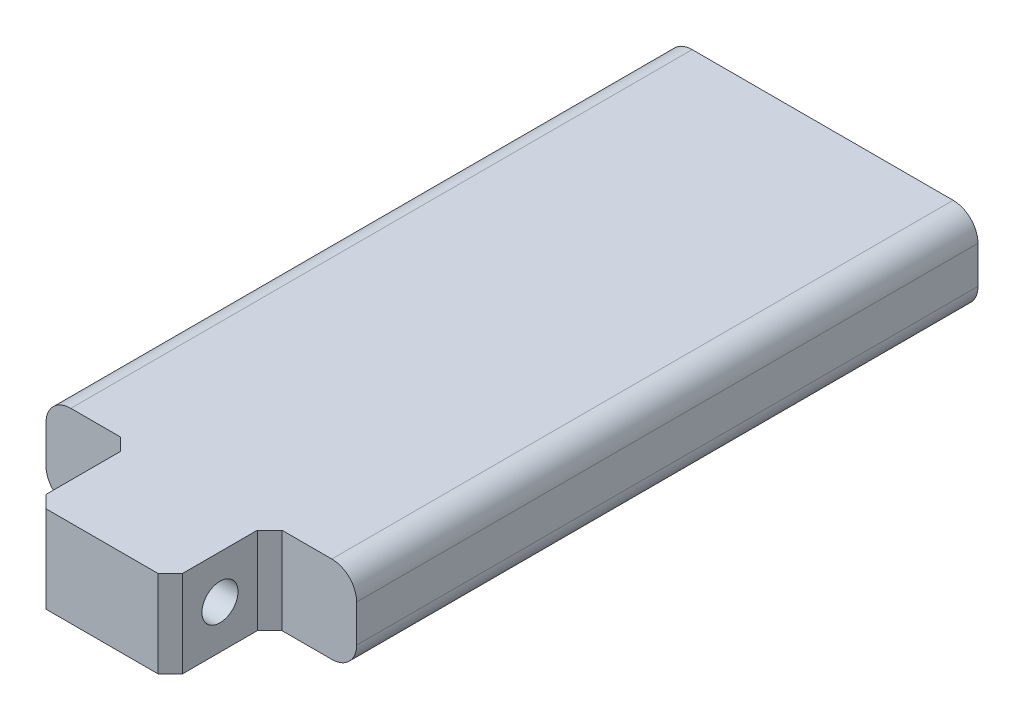
SolidWorks part; units mm, degrees
material "AISI 1020"
ref_plane "Front Plane" through (0, 0, 0) normal (0, 0, 1) x (1, 0, 0)
ref_plane "Top Plane" through (0, 0, 0) normal (0, 1, 0) x (1, 0, 0)
ref_plane "Right Plane" through (0, 0, 0) normal (1, 0, 0) x (0, 0, -1)
sketch "Sketch1" plane through (0, 0, 0) normal (0, 0, 1) x (1, 0, 0)
  line L1 (-12.5, -3.5) -> (12.5, -3.5)
  line L2 (-12.5, -3.5) -> (-12.5, 3.5)
  line L3 (-12.5, 3.5) -> (12.5, 3.5)
  line L4 (12.5, -3.5) -> (12.5, 3.5)
  line L5 (-12.5, -3.5) -> (12.5, 3.5) construction
  line L6 (-12.5, 3.5) -> (12.5, -3.5) construction
  point P0 (0, 0)
  dimension "D1" = 25
  dimension "D2" = 7
extrude "Boss-Extrude1" add sketch "Sketch1" along normal blind 58
sketch "Sketch2" plane through (0, 3.5, 0) normal (0, 1, 0) x (1, 0, 0)
  line L2 (-12.5, -58) -> (-5.5, -58)
  line L4 (-12.5, -58) -> (-12.5, -50)
  line L5 (-12.5, -50) -> (-5.5, -50)
  line L6 (-5.5, -58) -> (-5.5, -50)
  line L7 (12.5, -58) -> (5.5, -58)
  line L8 (12.5, -58) -> (12.5, -50)
  line L9 (12.5, -50) -> (5.5, -50)
  line L10 (5.5, -58) -> (5.5, -50)
  dimension "D1" = 8
  dimension "D2" = 7
extrude "Cut-Extrude1" cut sketch "Sketch2" against normal through all
hole_wizard "M3x0.5 Tapped Hole2" positions "Sketch5" profile "Sketch6" tap size "M3x0.5" standard "ANSI Metric"
sketch "Sketch5" plane through (0, 0, 0) normal (0, 0, -1) x (-1, 0, 0)
  line L0 (-12.5, 3.5) -> (12.5, 3.5) construction
  point P0 (-7, 0)
  point P2 (7, 0)
  dimension "D1" = 7
  dimension "D2" = 7
  dimension "D3" = 3.5
  dimension "D4" = 3.5
sketch "Sketch6" plane through (7, 0, 0) normal (1, 0, 0) x (0, 1, 0)
  line L0 (0, 0) -> (0, 8.2511)
  line L1 (0, 8.2511) -> (1.25, 7.5)
  line L2 (1.25, 7.5) -> (1.25, 0)
  line L5 (1.25, 0) -> (0, 0)
  line L10 (0, 8.2511) -> (-1.25, 7.5) construction
  line L11 (0, -6.35) -> (0, 107.95) construction
  dimension "Tap Drill Dia." = 2.5
  dimension "Tap Drill Depth" = 7.5
  dimension "Drill Angle" = 118
cosmetic thread "Hole Thread3" parameters "D1"=6, "D2"=3
cosmetic thread "Hole Thread4" parameters "D1"=6, "D2"=3
chamfer "Chamfer1" distance 1 angle 45 2 edges at (5.5, 0, 58) (-5.5, 0, 58)
hole_wizard "M2.5 Clearance Hole1" positions "Sketch7" profile "Sketch8" hole size "M2.5" standard "ANSI Metric" end condition through all
sketch "Sketch7" plane through (-5.5, -6.575, -1.7065) normal (-1, 0, 0) x (0, 0, 1)
  point P0 (55.7065, 6.575)
sketch "Sketch8" plane through (-5.5, 0, 54) normal (0, 1, 0) x (0, 0, 1)
  line L0 (0, 0) -> (0, 18)
  line L1 (0, 18) -> (1.45, 18)
  line L2 (1.45, 18) -> (1.45, 0)
  line L5 (1.45, 0) -> (0, 0)
  line L11 (0, -6.35) -> (0, 107.95) construction
  dimension "Thru Hole Dia." = 2.9
  dimension "Thru Hole Depth" = 18
fillet "Fillet1" radius 2 4 edges at (12.5, 3.5, 25) (12.5, -3.5, 25) (-12.5, 3.5, 25) (-12.5, -3.5, 25)
chamfer "Chamfer2" distance 1 angle 45 2 edges at (5.5, 0, 50) (-5.5, 0, 50)
